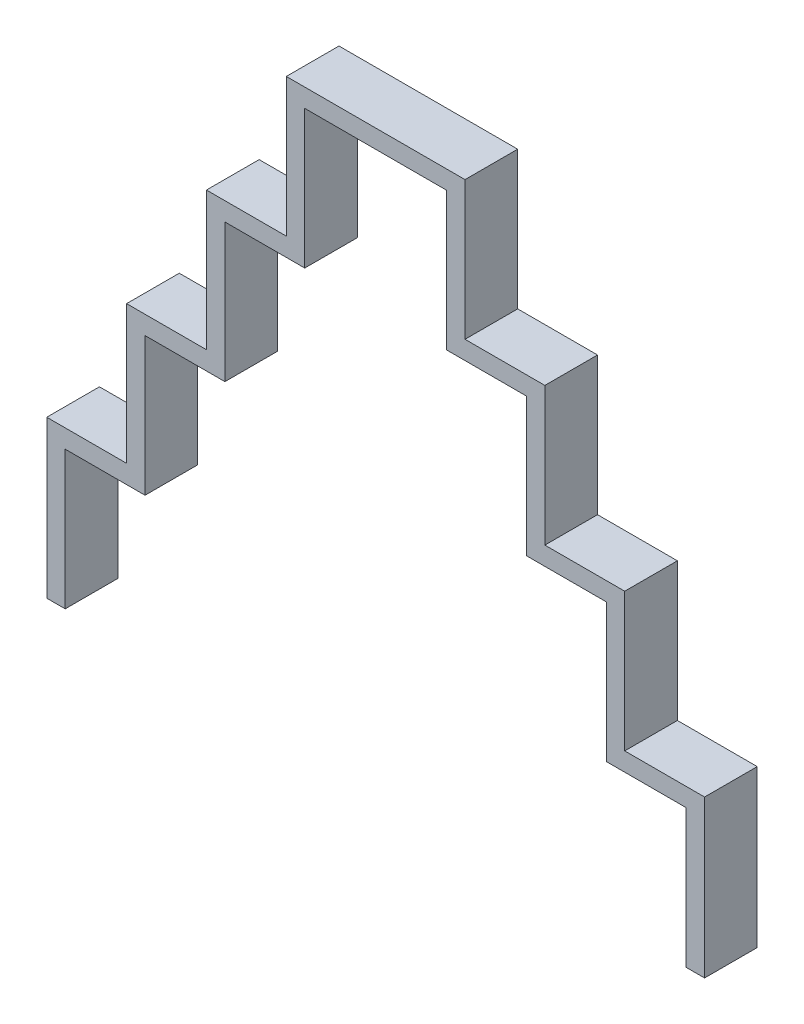
SolidWorks part; units mm, degrees
ref_plane "前视基准面" through (0, 0, 0) normal (0, 0, 1) x (1, 0, 0)
ref_plane "上视基准面" through (0, 0, 0) normal (0, 1, 0) x (1, 0, 0)
ref_plane "右视基准面" through (0, 0, 0) normal (1, 0, 0) x (0, 0, -1)
sketch "草图1" plane through (0, 0, 0) normal (0, 0, 1) x (1, 0, 0)
  line L0 (0, 20.4122) -> (-11.785, 0) construction
  line L1 (-11.785, 0) -> (11.785, 0) construction
  line L2 (11.785, 0) -> (0, 20.4122) construction
  line L3 (-2.6917, 21) -> (2.6917, 21)
  line L4 (-2.6917, 21) -> (-2.6917, 15.75)
  line L5 (-2.6917, 15.75) -> (-5.7228, 15.75)
  line L6 (-5.7228, 15.75) -> (-5.7228, 10.5)
  line L7 (-5.7228, 10.5) -> (-8.7539, 10.5)
  line L8 (-8.7539, 10.5) -> (-8.7539, 5.25)
  line L9 (-8.7539, 5.25) -> (-11.785, 5.25)
  line L10 (-11.785, 5.25) -> (-11.785, 0)
  line L11 (0, 0) -> (0, 23.214) construction
  line L12 (-11.785, 0) -> (11.785, 0) construction
  line L13 (0, -11.55) -> (0, 11.55) construction
  line L14 (0, 20.4122) -> (11.785, 0) construction
  line L15 (11.785, 5.25) -> (11.785, 0)
  line L16 (8.7539, 5.25) -> (11.785, 5.25)
  line L17 (8.7539, 10.5) -> (8.7539, 5.25)
  line L18 (5.7228, 10.5) -> (8.7539, 10.5)
  line L19 (5.7228, 15.75) -> (5.7228, 10.5)
  line L20 (2.6917, 15.75) -> (5.7228, 15.75)
  line L21 (2.6917, 21) -> (2.6917, 15.75)
  line L22 (-12.485, 5.95) -> (-12.485, 0)
  line L23 (-9.4539, 5.95) -> (-12.485, 5.95)
  line L24 (-9.4539, 11.2) -> (-9.4539, 5.95)
  line L25 (-6.4228, 11.2) -> (-9.4539, 11.2)
  line L26 (-6.4228, 16.45) -> (-6.4228, 11.2)
  line L27 (-3.3917, 16.45) -> (-6.4228, 16.45)
  line L28 (-3.3917, 21.7) -> (-3.3917, 16.45)
  line L29 (-3.3917, 21.7) -> (3.3917, 21.7)
  line L30 (3.3917, 21.7) -> (3.3917, 16.45)
  line L31 (3.3917, 16.45) -> (6.4228, 16.45)
  line L32 (6.4228, 16.45) -> (6.4228, 11.2)
  line L33 (6.4228, 11.2) -> (9.4539, 11.2)
  line L34 (9.4539, 11.2) -> (9.4539, 5.95)
  line L35 (9.4539, 5.95) -> (12.485, 5.95)
  line L36 (12.485, 5.95) -> (12.485, 0)
  line L37 (-12.485, 0) -> (-11.785, 0)
  line L38 (11.785, 0) -> (12.485, 0)
  point P17 (0, 0)
  point P24 (0, 21)
  dimension "D1" = 0.7
  dimension "D2" = 11.785
  dimension "D3" = 60
  dimension "D4" = 21
  dimension "D5" = 5.25
  dimension "D6" = 5.25
  dimension "D7" = 5.25
extrude "凸台-拉伸1" add sketch "草图1" along normal blind 2
